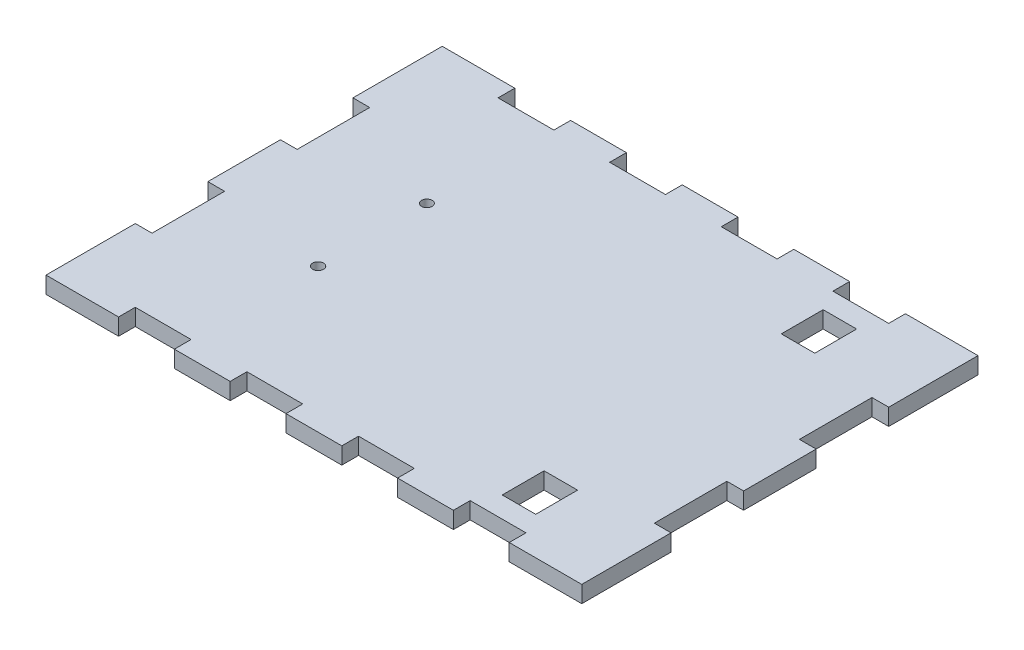
SolidWorks part; units mm, degrees
ref_plane "Front Plane" through (0, 0, 0) normal (0, 0, 1) x (1, 0, 0)
ref_plane "Top Plane" through (0, 0, 0) normal (0, 1, 0) x (1, 0, 0)
ref_plane "Right Plane" through (0, 0, 0) normal (1, 0, 0) x (0, 0, -1)
sketch "Sketch2" plane through (0, 0, 0) normal (0, 1, 0) x (1, 0, 0)
  line L0 (203.5046, 73.9886) -> (223.5046, 73.9886)
  line L2 (117.5046, 73.9886) -> (117.5046, 41.9886)
  line L4 (309.5046, 73.9886) -> (309.5046, 41.9886)
  line L5 (163.5046, 67.9886) -> (163.5046, -62.0114) construction
  line L6 (143.5046, 73.9886) -> (143.5046, 67.9886)
  line L7 (143.5046, 67.9886) -> (163.5046, 67.9886)
  line L8 (163.5046, 67.9886) -> (163.5046, 73.9886)
  line L9 (117.5046, 73.9886) -> (143.5046, 73.9886)
  line L11 (183.5046, 67.9886) -> (203.5046, 67.9886)
  line L12 (203.5046, 67.9886) -> (203.5046, 73.9886)
  line L17 (243.5046, 73.9886) -> (263.5046, 73.9886)
  line L18 (223.5046, 67.9886) -> (223.5046, 73.9886)
  line L19 (243.5046, 67.9886) -> (223.5046, 67.9886)
  line L20 (243.5046, 73.9886) -> (243.5046, 67.9886)
  line L21 (263.5046, 73.9886) -> (263.5046, 67.9886)
  line L22 (283.5046, 67.9886) -> (263.5046, 67.9886)
  line L23 (283.5046, 73.9886) -> (283.5046, 67.9886)
  line L25 (283.5046, 73.9886) -> (309.5046, 73.9886)
  line L26 (243.5046, -62.0114) -> (243.5046, -68.0114)
  line L27 (283.5046, -68.0114) -> (283.5046, -62.0114)
  line L28 (283.5046, -62.0114) -> (263.5046, -62.0114)
  line L29 (243.5046, -68.0114) -> (263.5046, -68.0114)
  line L30 (263.5046, -68.0114) -> (263.5046, -62.0114)
  line L31 (243.5046, -62.0114) -> (223.5046, -62.0114)
  line L32 (203.5046, -68.0114) -> (223.5046, -68.0114)
  line L33 (163.5046, 73.9886) -> (183.5046, 73.9886)
  line L34 (183.5046, 73.9886) -> (183.5046, 67.9886)
  line L35 (203.5046, -62.0114) -> (203.5046, -68.0114)
  line L36 (183.5046, -62.0114) -> (203.5046, -62.0114)
  line L37 (183.5046, -62.0114) -> (183.5046, -68.0114)
  line L38 (163.5046, -62.0114) -> (163.5046, -68.0114)
  line L39 (143.5046, -62.0114) -> (163.5046, -62.0114)
  line L40 (143.5046, -68.0114) -> (143.5046, -62.0114)
  line L41 (223.5046, -68.0114) -> (223.5046, -62.0114)
  line L42 (183.5046, -68.0114) -> (163.5046, -68.0114)
  line L43 (267.5046, -47.0114) -> (279.5046, -47.0114) construction
  line L44 (273.5046, -39.5114) -> (273.5046, -54.5114) construction
  line L45 (117.5046, -68.0114) -> (143.5046, -68.0114)
  line L46 (283.5046, -68.0114) -> (309.5046, -68.0114)
  line L48 (117.5046, 41.9886) -> (123.5046, 41.9886)
  line L49 (123.5046, 41.9886) -> (123.5046, 15.9886)
  line L50 (123.5046, 15.9886) -> (117.5046, 15.9886)
  line L51 (117.5046, -10.0114) -> (123.5046, -10.0114)
  line L52 (123.5046, -10.0114) -> (123.5046, -36.0114)
  line L53 (123.5046, -36.0114) -> (117.5046, -36.0114)
  line L54 (117.5046, 15.9886) -> (117.5046, -10.0114)
  line L55 (117.5046, -36.0114) -> (117.5046, -68.0114)
  line L56 (213.5046, 73.9886) -> (213.5046, 2.9886) construction
  line L57 (309.5046, 15.9886) -> (309.5046, -10.0114)
  line L58 (303.5046, -36.0114) -> (309.5046, -36.0114)
  line L59 (303.5046, -10.0114) -> (303.5046, -36.0114)
  line L60 (309.5046, -10.0114) -> (303.5046, -10.0114)
  line L61 (303.5046, 15.9886) -> (309.5046, 15.9886)
  line L62 (303.5046, 41.9886) -> (303.5046, 15.9886)
  line L63 (309.5046, 41.9886) -> (303.5046, 41.9886)
  line L64 (309.5046, 15.9886) -> (309.5046, -10.0114)
  line L65 (309.5046, -36.0114) -> (309.5046, -68.0114)
  line L66 (267.5046, -39.5114) -> (279.5046, -39.5114)
  line L67 (267.5046, -39.5114) -> (267.5046, -54.5114)
  line L68 (267.5046, -54.5114) -> (279.5046, -54.5114)
  line L69 (279.5046, -39.5114) -> (279.5046, -54.5114)
  line L74 (163.5046, 22.4886) -> (163.5046, -16.5114) construction
  line L75 (163.5046, -16.5114) -> (163.5046, 2.9886) construction
  line L77 (279.5046, 45.4886) -> (279.5046, 60.4886)
  line L78 (267.5046, 60.4886) -> (279.5046, 60.4886)
  line L79 (267.5046, 45.4886) -> (267.5046, 60.4886)
  line L80 (267.5046, 45.4886) -> (279.5046, 45.4886)
  circle A0 centre (163.5046, 22.4886) radius 1.9
  circle A1 centre (163.5046, -16.5114) radius 1.95
  point P63 (163.5046, 2.9886)
  point P67 (0, 0)
  dimension "D30" = 3.8
  dimension "D31" = 3.9
  dimension "D1" = 6
  dimension "D2" = 142
  dimension "D3" = 20
  dimension "D4" = 20
  dimension "D5" = 6
  dimension "D6" = 6
  dimension "D7" = 30
  dimension "D8" = 6
  dimension "D9" = 26
  dimension "D10" = 6
  dimension "D11" = 32
  dimension "D12" = 26
  dimension "D13" = 26
  dimension "D14" = 32
  dimension "D15" = 26
  dimension "D16" = 7.5
  dimension "D17" = 15
  dimension "D18" = 26
  dimension "12" = 12
  dimension "D19" = 7.5
  dimension "D20" = 15
  dimension "D21" = 26
  dimension "D22" = 20
  dimension "D23" = 20
  dimension "D24" = 20
  dimension "D25" = 6
  dimension "D26" = 6
  dimension "D27" = 30
  dimension "D28" = 6
  dimension "D29" = 39
  dimension "D32" = 0
  dimension "D33" = 6
  dimension "D34" = 6
  dimension "D35" = 6
  dimension "D36" = 20
  dimension "D37" = 20
  dimension "D38" = 20
  dimension "D39" = 20
  dimension "D40" = 6
  dimension "D41" = 20
  dimension "D42" = 20
  dimension "D43" = 6
  dimension "D44" = 20
  dimension "D45" = 20
  dimension "D46" = 6
  dimension "D47" = 6
  dimension "D48" = 6
  dimension "D49" = 12
  dimension "D50" = 12
extrude "Boss-Extrude2" add sketch "Sketch2" along normal blind 6 separate body contours L65 L58 L59 L60 L57 L61 L62 L63 L4 L25 L23 L22 L21 L17 L20 L19 L18 L0 L12 L11 L34 L33 L8 L7 L6 L9 L2 L48 L49 L50 L54 L51 L52 L53 L55 L45 L40 L39 L38 L42 L37 L36 L35 L32 L41 L31 L26 L29 L30 L28 L27
